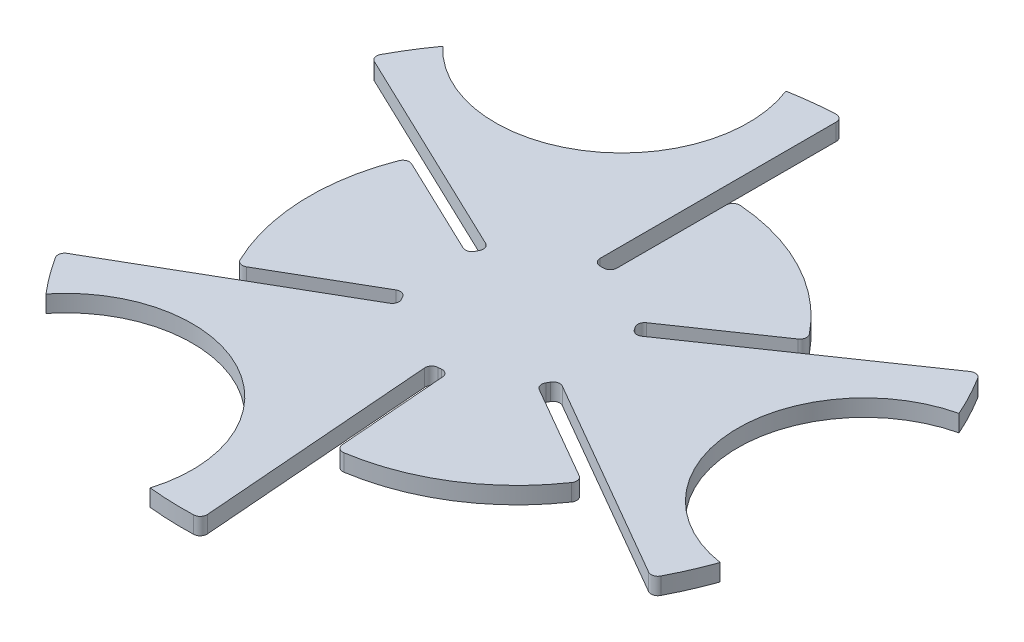
SolidWorks part; units mm, degrees
ref_plane "前基準面" through (0, 0, 0) normal (0, 0, 1) x (1, 0, 0)
ref_plane "上基準面" through (0, 0, 0) normal (0, 1, 0) x (1, 0, 0)
ref_plane "右基準面" through (0, 0, 0) normal (1, 0, 0) x (0, 0, -1)
sketch "草圖1" plane through (0, 0, 0) normal (0, 1, 0) x (1, 0, 0)
  line L2 (54.4665, -28.5595) -> (22.9006, -10.3349)
  line L8 (-2.5, 61.4492) -> (-2.5, 25)
  line L9 (-2.5, 25) -> (2.5, 25)
  line L10 (2.5, 61.4492) -> (2.5, 25)
  line L11 (22.9006, -10.3349) -> (20.4006, -14.6651)
  line L12 (51.9665, -32.8896) -> (20.4006, -14.6651)
  line L13 (-51.9665, -32.8896) -> (-20.4006, -14.6651)
  line L14 (-20.4006, -14.6651) -> (-22.9006, -10.3349)
  line L15 (-54.4665, -28.5595) -> (-22.9006, -10.3349)
  line L16 (20.6126, 14.1465) -> (0, 0) construction
  line L17 (4.4373, -24.7297) -> (7.2729, -61.0684)
  line L18 (22.0272, 12.0852) -> (52.0796, 32.7103)
  line L19 (19.1979, 16.2077) -> (49.2504, 36.8328)
  line L20 (19.1979, 16.2077) -> (22.0272, 12.0852)
  line L21 (-0.5475, -25.1187) -> (2.2881, -61.4574)
  line L22 (4.4373, -24.7297) -> (-0.5475, -25.1187)
  line L23 (-23.6352, 8.522) -> (-56.5233, 24.2357)
  line L24 (-21.4797, 13.0335) -> (-54.3677, 28.7472)
  line L25 (-23.6352, 8.522) -> (-21.4797, 13.0335)
  arc A35 (-2.5, 61.4492) -> (-54.3677, 28.7472) centre (0, 0) ccw
  circle A36 centre (0, 0) radius 25 construction
  arc A37 (54.4665, -28.5595) -> (52.0796, 32.7103) centre (0, 0) ccw
  arc A38 (-51.9665, -32.8896) -> (2.2881, -61.4574) centre (0, 0) ccw
  arc A39 (49.2504, 36.8328) -> (2.5, 61.4492) centre (0, 0) ccw
  arc A40 (-56.5233, 24.2357) -> (-54.4665, -28.5595) centre (0, 0) ccw
  arc A41 (7.2729, -61.0684) -> (51.9665, -32.8896) centre (0, 0) ccw
  point P1 (0, 25)
  dimension "D1" = 123
  dimension "D2" = 5
  dimension "D3" = 50
  dimension "D4" = 55.538
  dimension "D5" = 3
extrude "填料-伸長1" add sketch "草圖1" against normal blind 5
sketch "草圖2" plane through (0, 0, 0) normal (0, 1, 0) x (1, 0, 0)
  line L0 (-51.9665, -32.8896) -> (-84.4592, -51.6493)
  line L1 (2.2881, -61.4574) -> (5.2069, -98.863)
  line L2 (-46.125, -87.5984) -> (0, 0) construction
  line L3 (-0.5475, -25.1187) -> (2.2881, -61.4574) construction
  line L4 (-51.9665, -32.8896) -> (-20.4006, -14.6651) construction
  line L5 (-2.5, 61.4492) -> (-2.5, 98.9684)
  line L6 (-54.3677, 28.7472) -> (-88.2213, 44.9221)
  line L7 (54.4665, -28.5595) -> (86.9592, -47.3192)
  line L8 (52.0796, 32.7103) -> (83.0144, 53.9408)
  arc A0 (-75.3966, -64.1588) -> (-10.2353, -98.4695) centre (0, 0) ccw construction
  arc A1 (-10.2353, -98.4695) -> (-75.3966, -64.1588) centre (-46.125, -87.5984) ccw
  arc A2 (-80.1594, 58.0987) -> (-17.8648, 97.3748) centre (-52.8, 83.7446) ccw
  arc A3 (-84.4592, -51.6493) -> (-75.3966, -64.1588) centre (0, 0) ccw
  arc A4 (-10.2353, -98.4695) -> (5.2069, -98.863) centre (0, 0) ccw
  arc A5 (-51.9665, -32.8896) -> (2.2881, -61.4574) centre (0, 0) ccw construction
  arc A6 (-2.5, 98.9684) -> (-17.8648, 97.3748) centre (0, 0) ccw
  arc A7 (-80.1594, 58.0987) -> (-88.2213, 44.9221) centre (0, 0) ccw
  arc A8 (90.3947, 40.3707) -> (93.2614, -33.216) centre (98.925, 3.8538) ccw
  arc A9 (86.9592, -47.3192) -> (93.2614, -33.216) centre (0, 0) ccw
  arc A10 (90.3947, 40.3707) -> (83.0144, 53.9408) centre (0, 0) ccw
  arc A11 (-51.9665, -32.8896) -> (2.2881, -61.4574) centre (0, 0) ccw
  arc A12 (-2.5, 61.4492) -> (-54.3677, 28.7472) centre (0, 0) ccw
  arc A13 (54.4665, -28.5595) -> (52.0796, 32.7103) centre (0, 0) ccw
  dimension "D2" = 3
  dimension "D1" = 37.5
extrude "填料-伸長2" add sketch "草圖2" against normal up to surface (5 mm away) contours A11 L0 A3 A1 | A11 A1 A4 L1 | A13 L7 A9 A8 | A13 A8 A10 L8 | A12 L5 A6 A2 | A12 A2 A7 L6 up to face at (0, -5, 0)
fillet "圓角1" radius 2 24 edges at (-2.5, -2.5, -25) (2.5, -2.5, -25) (22.9006, -2.5, 10.3349) (20.4006, -2.5, 14.6651) (-20.4006, -2.5, 14.6651) (-22.9006, -2.5, 10.3349) (22.0272, -2.5, -12.0852) (19.1979, -2.5, -16.2077) (49.2504, -2.5, -36.8328) (2.5, -2.5, -61.4492) (-21.4797, -2.5, -13.0335) (-23.6352, -2.5, -8.522) (-56.5233, -2.5, -24.2357) (-54.4665, -2.5, 28.5595) (4.4373, -2.5, 24.7297) (-0.5475, -2.5, 25.1187) (7.2729, -2.5, 61.0684) (51.9665, -2.5, 32.8896) (86.9592, -2.5, 47.3192) (83.0144, -2.5, -53.9408) (-2.5, -2.5, -98.9684) (-88.2213, -2.5, -44.9221) (-84.4592, -2.5, 51.6493) (5.2069, -2.5, 98.863)
